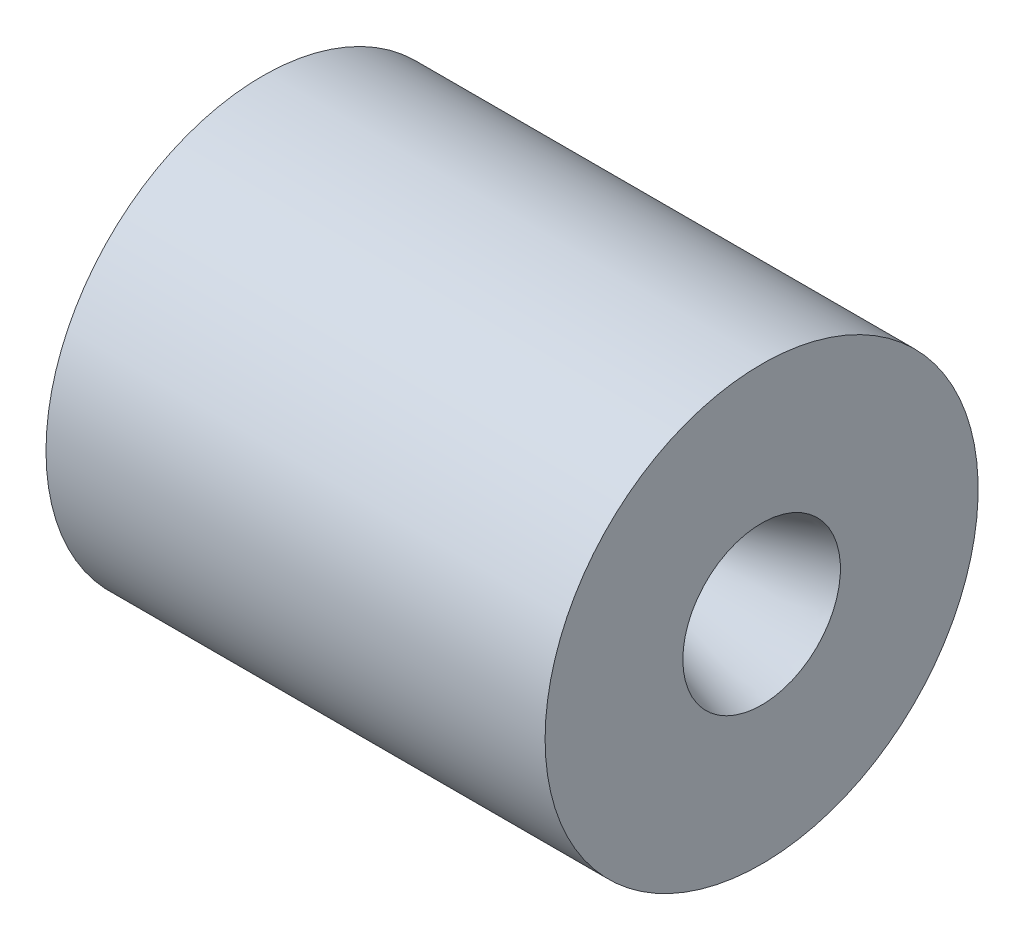
SolidWorks part; units mm, degrees
ref_plane "Front Plane" through (0, 0, 0) normal (0, 0, 1) x (1, 0, 0)
ref_plane "Top Plane" through (0, 0, 0) normal (0, 1, 0) x (1, 0, 0)
ref_plane "Right Plane" through (0, 0, 0) normal (1, 0, 0) x (0, 0, -1)
sketch "Model" plane through (0, 0, 0) normal (0, 0, 1) x (1, 0, 0)
  line L0 (0, 55.1403) -> (23.151, 55.1403)
  line L1 (95.1514, 35.8478) -> (128.5669, 16.5553)
  line L2 (0, 0) -> (185.6492, 0) construction
  line L3 (0, 55.1403) -> (0, 80.5403)
  line L4 (0, 80.5403) -> (185.6492, 80.5403)
  line L5 (185.6492, 80.5403) -> (185.6492, 29.3103)
  arc A0 (95.1514, 35.8478) -> (23.151, 55.1403) centre (23.151, -88.8606) ccw
  arc A1 (128.5669, 16.5553) -> (138.9057, 13.7851) centre (138.9057, 34.4627) ccw
  arc A2 (138.9057, 13.7851) -> (140.6089, 14.0681) centre (138.9057, 19.051) ccw
  spline S0 degree 2 poles (140.6089, 14.0681) (181.4601, 28.0309) (185.6492, 29.3103) knots 0 0 0 1 1 1
  dimension "D1" = 55.1403
  dimension "D2" = 25.4
revolve "Revolve1" add sketch "Model" angle 360 about L2
hole_wizard "13/64 (0.20313) Diameter Hole1" positions "Sketch2" profile "Sketch3" hole size "13/64" standard "ANSI Inch"
sketch "Sketch2" plane through (0, 0, 0) normal (-1, 0, 0) x (0, 0, 1)
  point P0 (71.5, 0)
  dimension "D1" = 71.5
sketch "Sketch3" plane through (0, 0, 71.5) normal (0, 1, 0) x (0, 0, 1)
  line L0 (0, 0) -> (0, 14.2501)
  line L1 (0, 14.2501) -> (2.5798, 12.7)
  line L2 (2.5798, 12.7) -> (2.5798, 0)
  line L5 (2.5798, 0) -> (0, 0)
  line L10 (0, 14.2501) -> (-2.5798, 12.7) construction
  line L11 (0, -6.35) -> (0, 107.95) construction
  dimension "Hole Dia." = 5.1595
  dimension "Hole Depth" = 12.7
  dimension "Drill Angle" = 118
pattern_circular "CirPattern1" count 15 over 360 about axis through (0, 0, 0) along (1, 0, 0) of "13/64 (0.20313) Diameter Hole1"
